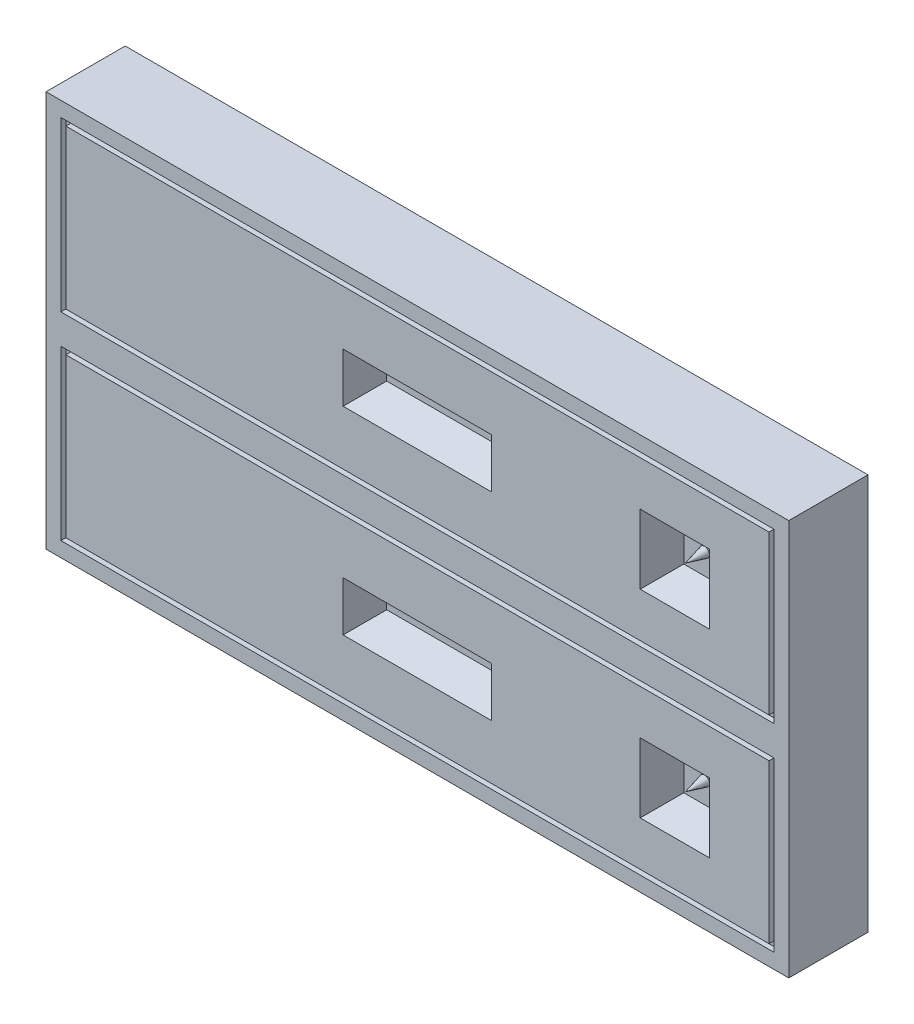
SolidWorks part; units mm, degrees
ref_plane "Front Plane" through (0, 0, 0) normal (0, 0, 1) x (1, 0, 0)
ref_plane "Top Plane" through (0, 0, 0) normal (0, 1, 0) x (1, 0, 0)
ref_plane "Right Plane" through (0, 0, 0) normal (1, 0, 0) x (0, 0, -1)
sketch "Sketch1" plane through (0, 0, 0) normal (0, 0, 1) x (1, 0, 0)
  line L1 (0, 0) -> (75, 0)
  line L2 (0, 0) -> (0, 40)
  line L3 (0, 40) -> (75, 40)
  line L4 (75, 0) -> (75, 40)
  dimension "D1" = 40
  dimension "D2" = 75
extrude "Boss-Extrude1" add sketch "Sketch1" along normal blind 8
sketch "Sketch2" plane through (0, 0, 8) normal (0, 0, 1) x (1, 0, 0)
  line L0 (0, 20) -> (75, 20) construction
  line L1 (0, 40) -> (0, 0) construction
  line L2 (75, 0) -> (75, 40) construction
  line L3 (0, 0) -> (75, 0) construction
  line L4 (2, 18) -> (73, 18)
  line L5 (2, 18) -> (2, 2)
  line L6 (2, 2) -> (73, 2)
  line L7 (73, 18) -> (73, 2)
  line L8 (1.5, 18.5) -> (73.5, 18.5)
  line L9 (73.5, 18.5) -> (73.5, 1.5)
  line L10 (1.5, 1.5) -> (73.5, 1.5)
  line L11 (1.5, 18.5) -> (1.5, 1.5)
  dimension "D1" = 2
  dimension "D2" = 2
  dimension "D3" = 2
  dimension "D4" = 2
  dimension "D5" = 0.5
extrude "Cut-Extrude1" cut sketch "Sketch2" against normal blind 0.5
sketch "Sketch3" plane through (0, 0, 8) normal (0, 0, 1) x (1, 0, 0)
  line L0 (2, 10) -> (73, 10) construction
  line L1 (2, 18) -> (2, 2) construction
  line L2 (73, 2) -> (73, 18) construction
  line L3 (0, 40) -> (0, 0) construction
  line L4 (30, 12.5) -> (45, 12.5)
  line L5 (30, 12.5) -> (30, 7.5)
  line L6 (30, 7.5) -> (45, 7.5)
  line L7 (45, 12.5) -> (45, 7.5)
  line L9 (60, 13.5) -> (67, 13.5)
  line L10 (60, 13.5) -> (60, 6.5)
  line L11 (60, 6.5) -> (67, 6.5)
  line L12 (67, 13.5) -> (67, 6.5)
  point P10 (30, 10)
  point P17 (60, 10)
  dimension "D1" = 30
  dimension "D2" = 15
  dimension "D3" = 5
  dimension "D4" = 15
  dimension "D5" = 7
  dimension "D6" = 7
extrude "Cut-Extrude3" cut sketch "Sketch3" against normal blind 3
draft "Draft4" type of draft neutral plane draft angle 25 faces to draft 4 face at (45, 10, 6.5) face at (37.5, 7.5, 6.5) face at (30, 10, 6.5) face at (37.5, 12.5, 6.5) neutral plane through (0, 0, 8) neutral plane normal (0, 0, 1) parameters "D1"=25
draft "Draft5" type of draft neutral plane draft angle 25 faces to draft 4 face at (67, 10, 6.5) face at (63.5, 6.5, 6.5) face at (60, 10, 6.5) face at (63.5, 13.5, 6.5) neutral plane through (0, 0, 8) neutral plane normal (0, 0, 1) parameters "D1"=25
ref_plane "Plane1" through (63.5, 0, 0) normal (1, 0, 0) x (0, 0, -1)
sketch "Sketch7" plane through (63.5, 0, 0) normal (1, 0, 0) x (0, 0, -1)
  line L0 (-5, 12.1011) -> (-5, 7.8989) construction
  line L1 (-5, 10) -> (-5, 9.5)
  line L2 (-5, 9.5) -> (-6.9365, 10)
  line L3 (-6.9365, 10) -> (-5, 10)
  point P0 (-5, 10)
  dimension "D1" = 2
  dimension "D2" = 0.5
revolve "Revolve2" add sketch "Sketch7" angle 360 about L3
ref_plane "Plane2" through (0, 20, 0) normal (0, 1, 0) x (1, 0, 0)
mirror "Mirror1" about plane through (0, 20, 0) normal (0, 1, 0) of "Revolve2", "Draft5", "Draft4", "Cut-Extrude1", "Cut-Extrude3"
